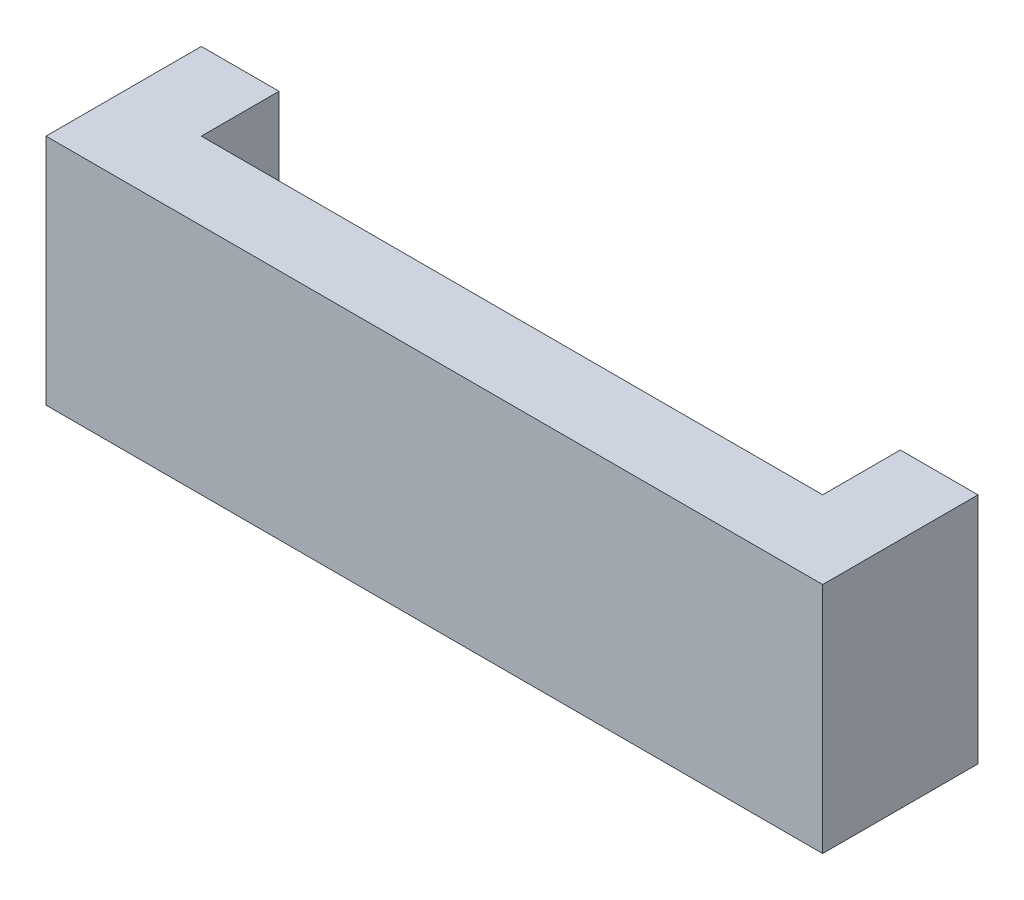
SolidWorks part; units mm, degrees
ref_plane "Přední rovina" through (0, 0, 0) normal (0, 0, 1) x (1, 0, 0)
ref_plane "Horní rovina" through (0, 0, 0) normal (0, 1, 0) x (1, 0, 0)
ref_plane "Pravá rovina" through (0, 0, 0) normal (1, 0, 0) x (0, 0, -1)
sketch "Sketch1" plane through (0, 0, 0) normal (0, 1, 0) x (1, 0, 0)
  line L1 (-50, 0) -> (-40, 0)
  line L2 (-50, 0) -> (-50, -20)
  line L3 (-50, -20) -> (50, -20)
  line L6 (-40, 0) -> (-40, -10)
  line L7 (-40, -10) -> (40, -10)
  line L9 (0, 0) -> (0, -20) construction
  line L10 (40, 0) -> (40, -10)
  line L11 (50, 0) -> (50, -20)
  line L12 (50, 0) -> (40, 0)
  point P3 (0, -10)
  dimension "D1" = 50
  dimension "D2" = 10
  dimension "D3" = 10
  dimension "D4" = 10
extrude "Boss-Extrude1" add sketch "Sketch1" along normal blind 30
